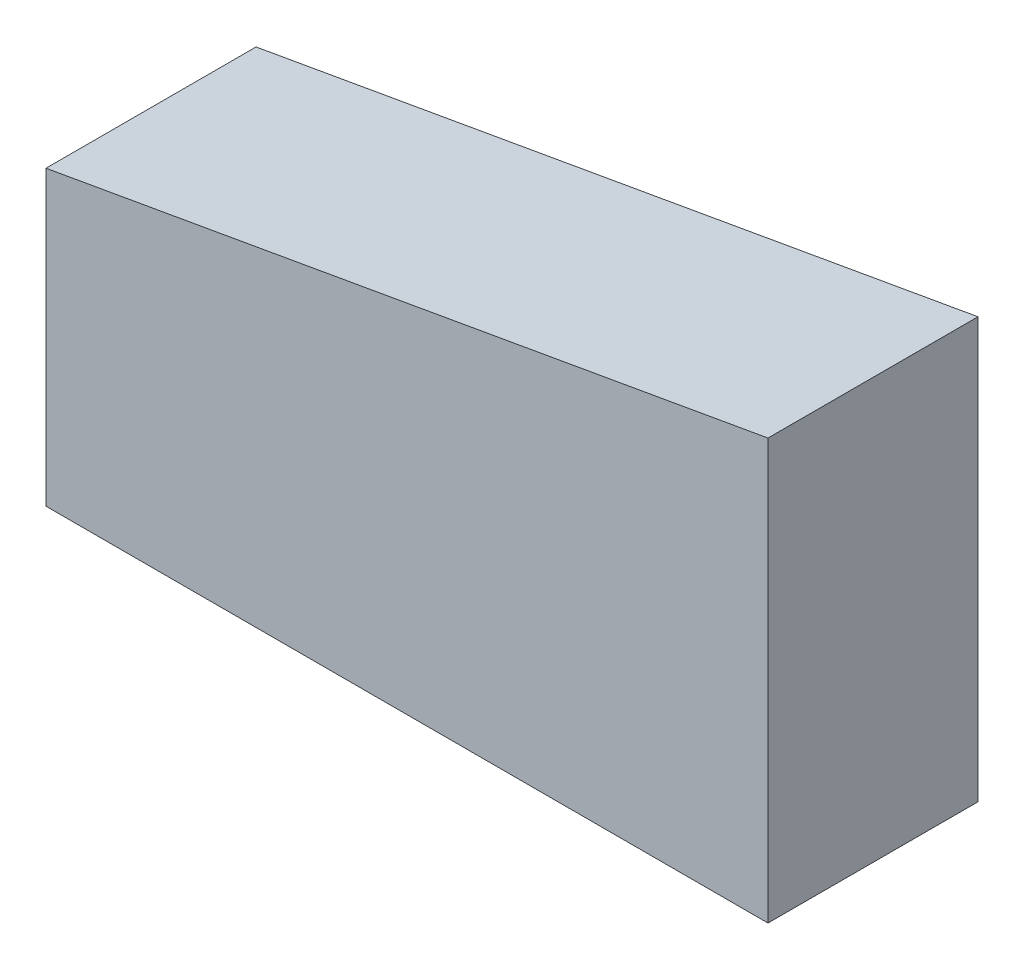
SolidWorks part; units mm, degrees
ref_plane "Plan de face" through (0, 0, 0) normal (0, 0, 1) x (1, 0, 0)
ref_plane "Plan de dessus" through (0, 0, 0) normal (0, 1, 0) x (1, 0, 0)
ref_plane "Plan de droite" through (0, 0, 0) normal (1, 0, 0) x (0, 0, -1)
sketch "Esquisse1" plane through (0, 0, 0) normal (0, 0, 1) x (1, 0, 0)
  line L0 (-27.5, 0) -> (27.5, 0)
  line L1 (27.5, 0) -> (27.5, 32)
  line L2 (27.5, 32) -> (-27.5, 22.302)
  line L3 (-27.5, 22.302) -> (-27.5, 0)
  line L4 (-27.5, 0) -> (-27.5, 46.8255) construction
  point P4 (0, 0)
  dimension "D1" = 55
  dimension "D2" = 32
  dimension "D3" = 80
extrude "Boss.-Extru.1" add sketch "Esquisse1" along normal mid plane 16
